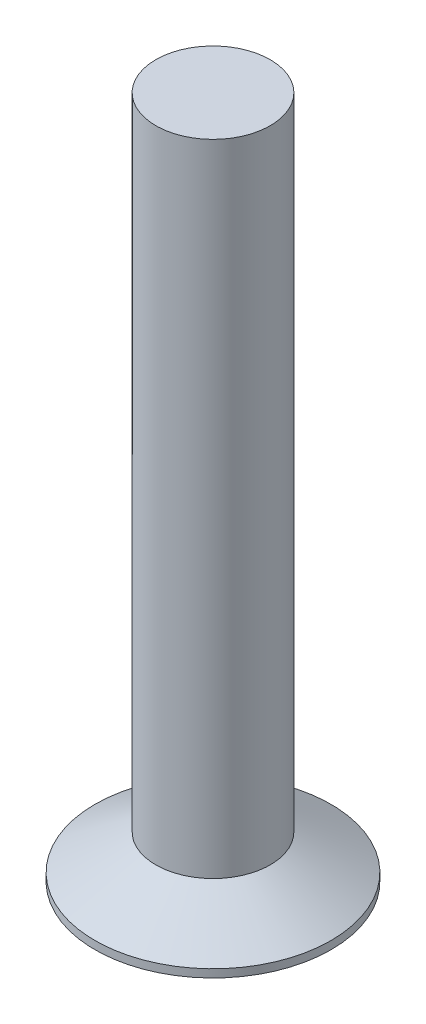
SolidWorks part; units mm, degrees
ref_plane "Front Plane" through (0, 0, 0) normal (0, 0, 1) x (1, 0, 0)
ref_plane "Top Plane" through (0, 0, 0) normal (0, 1, 0) x (1, 0, 0)
ref_plane "Right Plane" through (0, 0, 0) normal (1, 0, 0) x (0, 0, -1)
sketch "Sketch1" plane through (0, 0, 0) normal (0, 0, 1) x (1, 0, 0)
  line L0 (0.0094, 4.3599) -> (0.0094, -47.8659) construction
  line L5 (0.0094, -37.1475) -> (-14.7406, -37.1475)
  line L6 (-14.7406, -37.1475) -> (-14.7406, -36.1475)
  line L7 (-14.7406, -36.1475) -> (-7.1406, -31.7597)
  line L8 (0.0094, -31.9672) -> (0.0094, -37.1475)
  line L10 (-7.1406, 48.2403) -> (0.0094, 48.2403)
  line L11 (-7.1406, 48.2403) -> (-7.1406, -31.7597)
  line L13 (0.0094, 48.2403) -> (0.0094, -31.9672)
  dimension "D1" = 14.75
  dimension "D2" = 1
  dimension "D3" = 120
  dimension "D4" = 80
  dimension "D5" = 7.15
revolve "Revolve1" add sketch "Sketch1" angle 360 about L0
